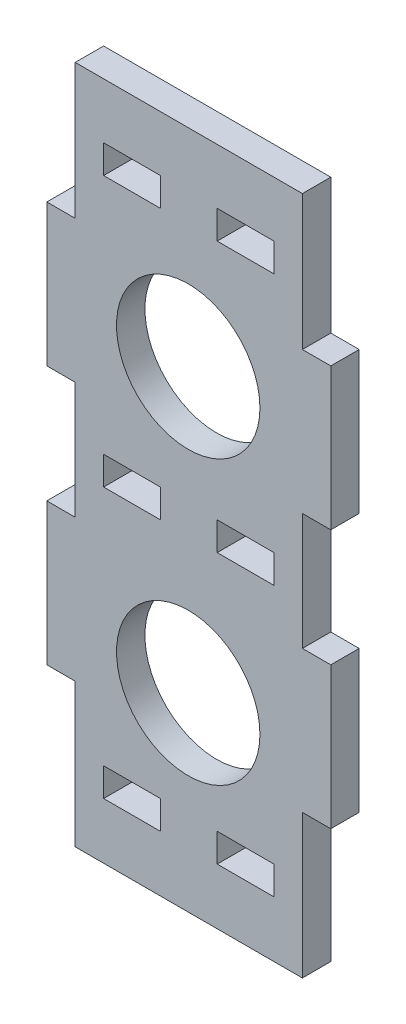
SolidWorks part; units mm, degrees
ref_plane "前视基准面" through (0, 0, 0) normal (0, 0, 1) x (1, 0, 0)
ref_plane "上视基准面" through (0, 0, 0) normal (0, 1, 0) x (1, 0, 0)
ref_plane "右视基准面" through (0, 0, 0) normal (1, 0, 0) x (0, 0, -1)
sketch "Model" plane through (0, 0, 0) normal (0, 0, 1) x (1, 0, 0)
  line L1 (913.1843, 571.9071) -> (913.1843, 563.674)
  line L2 (913.1843, 563.674) -> (915.1843, 563.674)
  line L3 (915.1843, 563.674) -> (915.1843, 553.674)
  line L4 (915.1843, 553.674) -> (913.1843, 553.674)
  line L5 (913.1843, 553.674) -> (913.1843, 543.5703)
  line L6 (913.1843, 543.5703) -> (897.1843, 543.5703)
  line L7 (897.1843, 543.5703) -> (897.1843, 553.674)
  line L8 (897.1843, 553.674) -> (895.1843, 553.674)
  line L9 (895.1843, 553.674) -> (895.1843, 563.674)
  line L10 (895.1843, 563.674) -> (897.1843, 563.674)
  line L11 (897.1843, 563.674) -> (897.1843, 571.9071)
  line L13 (897.1824, 581.9071) -> (897.1843, 591.4197)
  line L14 (897.1843, 591.4197) -> (913.1843, 591.4197)
  line L15 (913.1843, 591.4197) -> (913.1843, 581.9071)
  line L16 (895.1843, 571.9071) -> (895.1843, 581.9071)
  line L17 (911.1843, 585.5181) -> (911.1843, 587.5181)
  line L18 (907.1843, 585.5181) -> (907.1843, 587.5181)
  line L19 (903.1843, 585.5181) -> (903.1843, 587.5181)
  line L20 (899.1843, 585.5181) -> (899.1843, 587.5181)
  line L21 (911.1843, 566.5181) -> (911.1843, 568.5181)
  line L22 (907.1843, 566.5181) -> (907.1843, 568.5181)
  line L23 (903.1843, 566.5181) -> (903.1843, 568.5181)
  line L24 (899.1843, 566.5181) -> (899.1843, 568.5181)
  line L25 (911.1843, 547.5181) -> (911.1843, 549.5181)
  line L26 (907.1843, 547.5181) -> (907.1843, 549.5181)
  line L27 (903.1843, 547.5181) -> (903.1843, 549.5181)
  line L28 (899.1843, 547.5181) -> (899.1843, 549.5181)
  line L29 (913.1843, 581.9071) -> (915.1843, 581.9071)
  line L30 (915.1843, 571.9071) -> (913.1843, 571.9071)
  line L31 (911.1843, 587.5181) -> (907.1843, 587.5181)
  line L32 (911.1843, 585.5181) -> (907.1843, 585.5181)
  line L33 (903.1843, 585.5181) -> (899.1843, 585.5181)
  line L34 (903.1843, 587.5181) -> (899.1843, 587.5181)
  line L35 (911.1843, 566.5181) -> (907.1843, 566.5181)
  line L36 (911.1843, 568.5181) -> (907.1843, 568.5181)
  line L37 (903.1843, 568.5181) -> (899.1843, 568.5181)
  line L38 (903.1843, 566.5181) -> (899.1843, 566.5181)
  line L39 (911.1843, 549.5181) -> (907.1843, 549.5181)
  line L40 (911.1843, 547.5181) -> (907.1843, 547.5181)
  line L41 (903.1843, 549.5181) -> (899.1843, 549.5181)
  line L42 (903.1843, 547.5181) -> (899.1843, 547.5181)
  line L43 (897.1843, 571.9071) -> (895.1843, 571.9071)
  line L44 (897.1824, 581.9071) -> (895.1843, 581.9071)
  line L45 (915.1843, 581.9071) -> (915.1843, 571.9071)
  circle A0 centre (905.1437, 556.9355) radius 5.0509
  circle A1 centre (905.1437, 576.8451) radius 5.0509
extrude "凸台-拉伸1" add sketch "Model" along normal blind 2
